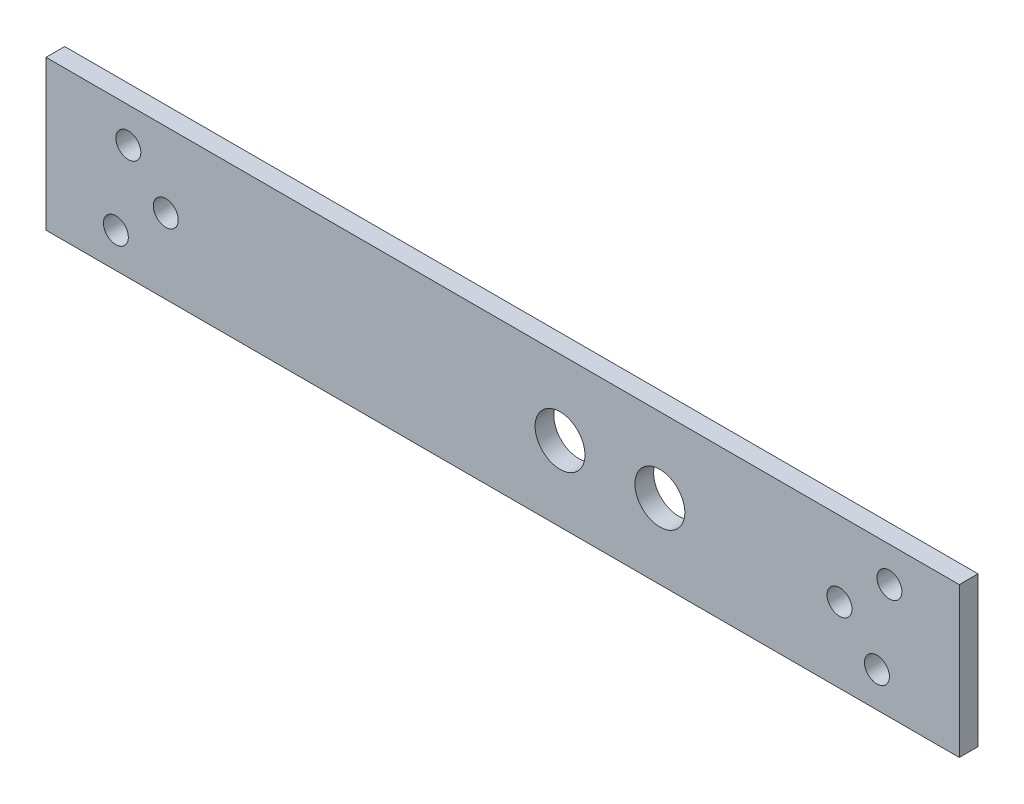
SolidWorks part; units mm, degrees
ref_plane "Front Plane" through (0, 0, 0) normal (0, 0, 1) x (1, 0, 0)
ref_plane "Top Plane" through (0, 0, 0) normal (0, 1, 0) x (1, 0, 0)
ref_plane "Right Plane" through (0, 0, 0) normal (1, 0, 0) x (0, 0, -1)
sketch "Sketch1" plane through (0, 0, 0) normal (0, 0, 1) x (1, 0, 0)
  line L0 (38.1, 38.1) -> (38.1, 0) construction
  line L1 (0, 0) -> (232.41, 0)
  line L2 (0, 0) -> (0, 38.1)
  line L3 (0, 38.1) -> (232.41, 38.1)
  line L4 (232.41, 0) -> (232.41, 38.1)
  line L5 (194.31, 38.1) -> (194.31, 0) construction
  circle A0 centre (30.48, 19.05) radius 3.175
  circle A2 centre (156.21, 19.05) radius 6.35
  circle A3 centre (20.955, 29.21) radius 3.175
  circle A4 centre (17.78, 8.89) radius 3.175
  circle A5 centre (214.63, 29.21) radius 3.175
  circle A6 centre (201.93, 19.05) radius 3.175
  circle A7 centre (211.455, 8.89) radius 3.175
  circle A8 centre (130.81, 19.05) radius 6.35
  point P9 (0, 19.05)
  point P16 (38.1, 19.05)
  dimension "D3" = 6.35
  dimension "D15" = 12.7
  dimension "D1" = 232.41
  dimension "D2" = 38.1
  dimension "D4" = 38.1
  dimension "D5" = 7.62
  dimension "D6" = 101.6
  dimension "D7" = 20.32
  dimension "D8" = 8.89
  dimension "D9" = 8.89
  dimension "D10" = 17.145
  dimension "D11" = 20.32
  dimension "D12" = 17.145
  dimension "D13" = 7.62
  dimension "D14" = 38.1
  dimension "D16" = 25.4
extrude "Boss-Extrude1" add sketch "Sketch1" along normal blind 4.7625
